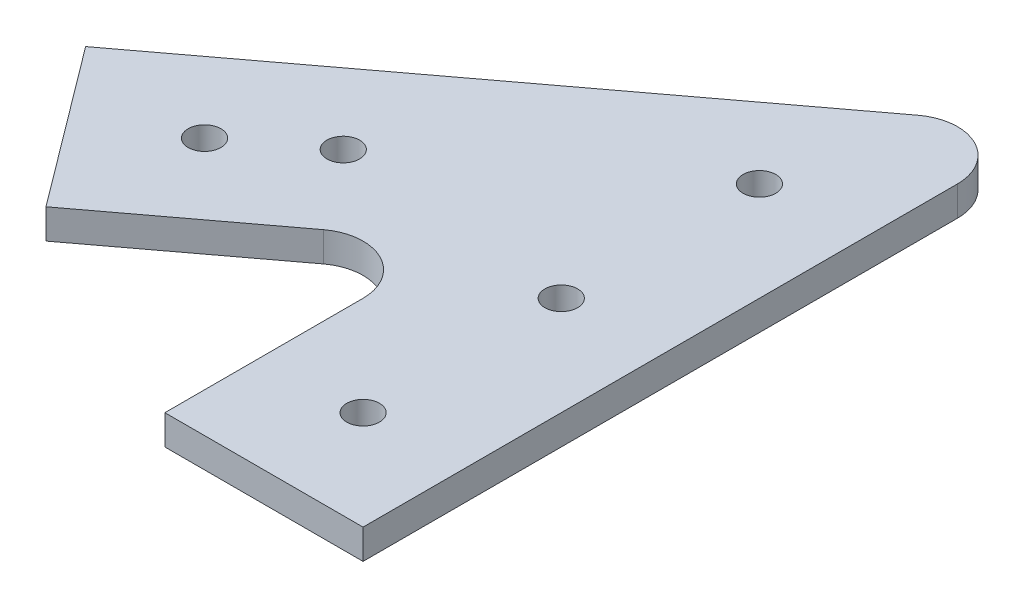
SolidWorks part; units mm, degrees
ref_plane "前视基准面" through (0, 0, 0) normal (0, 0, 1) x (1, 0, 0)
ref_plane "上视基准面" through (0, 0, 0) normal (0, 1, 0) x (1, 0, 0)
ref_plane "右视基准面" through (0, 0, 0) normal (1, 0, 0) x (0, 0, -1)
other "Configuration Table"
sketch "草图1" plane through (0, 0, 0) normal (0, 1, 0) x (1, 0, 0)
  line L0 (-22.3327, -14.6649) -> (17.6675, 15.3352) construction
  line L1 (-28.3327, -6.6649) -> (-16.3327, -22.6649)
  line L2 (-16.3327, -22.6649) -> (7.6673, -4.6649)
  line L3 (7.664, -34.6648) -> (27.664, -34.6648)
  line L4 (-28.3327, -6.6649) -> (-4.3327, 11.3351)
  line L5 (-4.3327, 11.3351) -> (27.6645, 35.333)
  line L6 (27.6645, 35.333) -> (27.664, -34.6648)
  line L7 (7.664, -34.6648) -> (7.6673, -4.6649)
  circle A0 centre (17.6675, 15.3352) radius 1.65
  circle A1 centre (17.6675, -4.6648) radius 1.65
  circle A2 centre (17.6675, -24.6648) radius 1.65
  circle A3 centre (-6.3327, -2.6649) radius 1.65
  circle A4 centre (-14.3327, -8.6649) radius 1.65
  dimension "D1" = 20
  dimension "D2" = 20
  dimension "D3" = 10
  dimension "D4" = 9.9966
  dimension "D5" = 10
  dimension "D6" = 10
extrude "凸台-拉伸1" add sketch "草图1" along normal blind 3
fillet "圆角2" radius 5 1 edges at (7.6673, 1.5, 4.6649)
fillet "圆角3" radius 5 1 edges at (27.6645, 1.5, -35.333)
